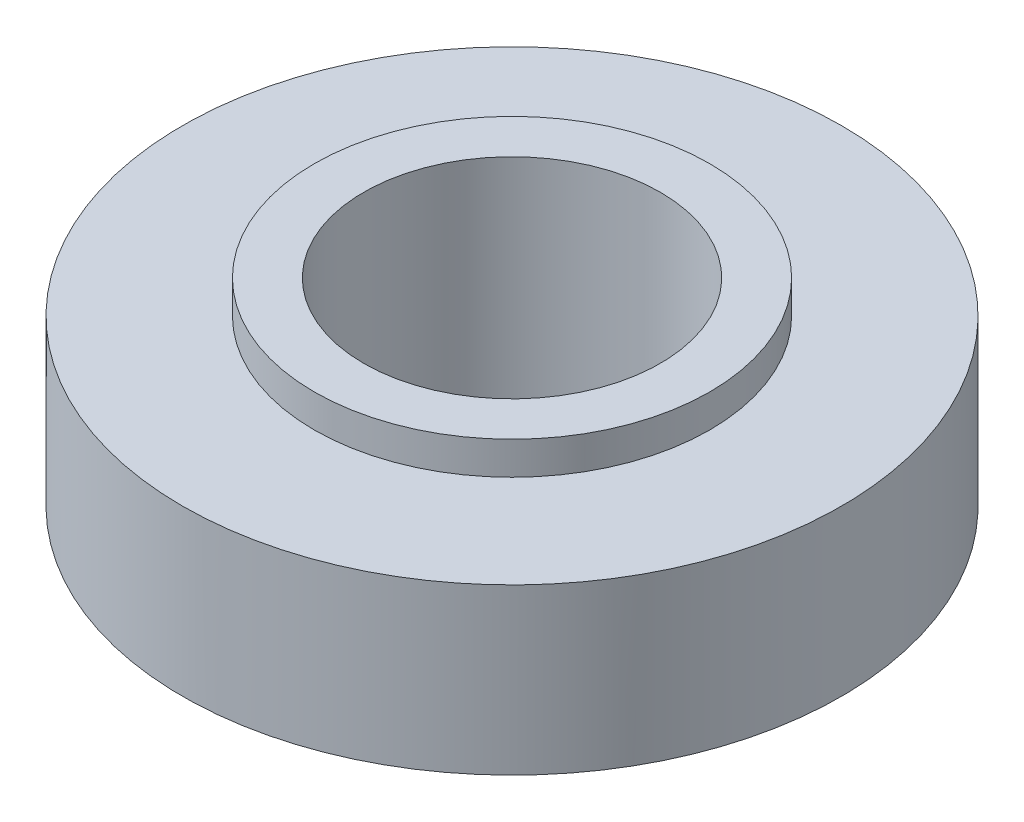
SolidWorks part; units mm, degrees
ref_plane "Front Plane" through (0, 0, 0) normal (0, 0, 1) x (1, 0, 0)
ref_plane "Top Plane" through (0, 0, 0) normal (0, 1, 0) x (1, 0, 0)
ref_plane "Right Plane" through (0, 0, 0) normal (1, 0, 0) x (0, 0, -1)
sketch "Sketch2" plane through (0, 0, 0) normal (0, 1, 0) x (1, 0, 0)
  circle A0 centre (0, 0) radius 10
  circle A1 centre (0, 0) radius 4.5
  dimension "D1" = 20
  dimension "D2" = 9
extrude "Boss-Extrude1" add sketch "Sketch2" along normal mid plane 7
sketch "Sketch3" plane through (0, 3.5, 0) normal (0, 1, 0) x (1, 0, 0)
  circle A0 centre (0, 0) radius 13
  circle A1 centre (0, 0) radius 6
  dimension "D1" = 26
  dimension "D2" = 12
extrude "Cut-Extrude1" cut sketch "Sketch3" against normal blind 1
mirror "Mirror3" about plane through (0, 0, 0) normal (0, 1, 0) of "Cut-Extrude1"
